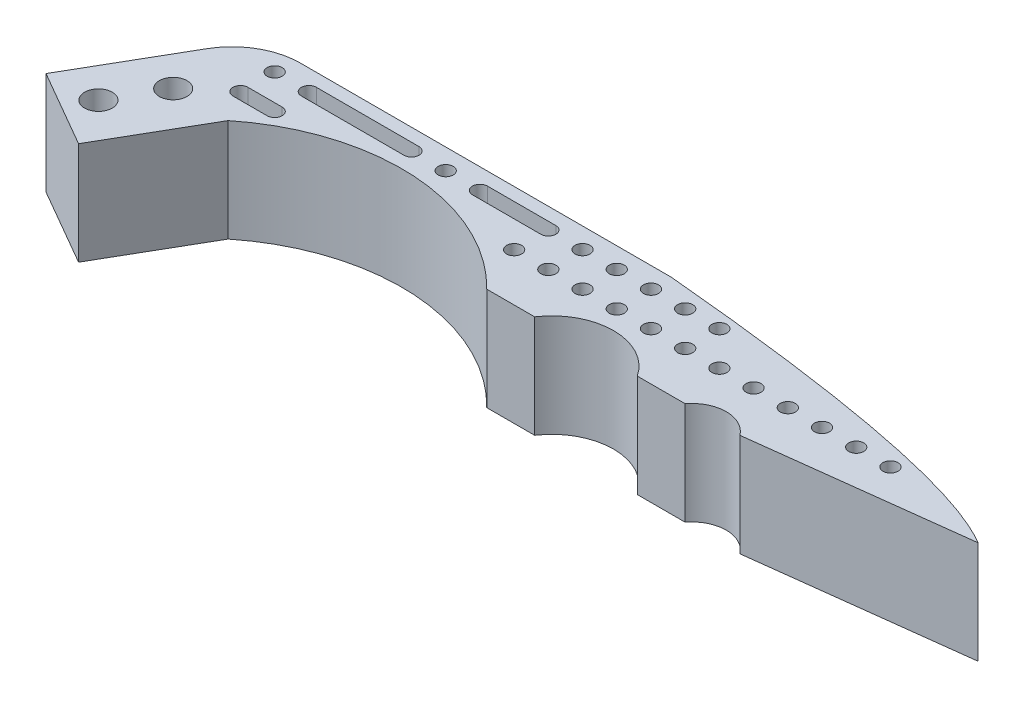
SolidWorks part; units mm, degrees
ref_plane "前视基准面" through (0, 0, 0) normal (0, 0, 1) x (1, 0, 0)
ref_plane "上视基准面" through (0, 0, 0) normal (0, 1, 0) x (1, 0, 0)
ref_plane "右视基准面" through (0, 0, 0) normal (1, 0, 0) x (0, 0, -1)
other "Configuration Table"
sketch "草图1" plane through (0, 0, 0) normal (0, 1, 0) x (1, 0, 0)
  line L0 (0, 0) -> (60, 0)
  line L1 (60, 0) -> (120, 0) construction
  line L2 (120, 0) -> (120, -15) construction
  line L3 (60, 0) -> (115, -5) construction
  line L4 (115, -5) -> (120, -15) construction
  line L5 (120, -15) -> (85, -15)
  line L6 (85, -15) -> (77, -15) construction
  line L7 (77, -15) -> (70, -15)
  line L8 (70, -15) -> (55, -15)
  line L9 (55, -15) -> (48, -15)
  line L10 (0, 0) -> (0, -24.7218) construction
  line L11 (0, 0) -> (-11.5, -19.9186)
  line L16 (-11.5, -19.9186) -> (-0.2417, -26.4186)
  line L17 (-0.2417, -26.4186) -> (7.7583, -12.5622)
  arc A0 (55, -15) -> (70, -15) centre (62.5, -19.9749) cw
  arc A1 (77, -15) -> (85, -15) centre (81, -18) cw
  arc A2 (7.7583, -12.5622) -> (48, -15) centre (26.5356, -35.959) cw
  spline S0 degree 2 poles (60, 0) (115, -5) (120, -15) knots 0 0 0 1 1 1
  point P3 (81, -15)
  dimension "D9" = 15
  dimension "D12" = 7
  dimension "D13" = 13
  dimension "D11" = 23
  dimension "D10" = 30
  dimension "D14" = 16
  dimension "D1" = 60
  dimension "D2" = 60
  dimension "D3" = 5
  dimension "D4" = 5
  dimension "D5" = 15
  dimension "D6" = 35
  dimension "D7" = 8
  dimension "D8" = 7
extrude "凸台-拉伸1" add sketch "草图1" along normal blind 15
sketch "草图2" plane through (0, 15, 0) normal (0, 1, 0) x (1, 0, 0)
  line L1 (120, -15) -> (85, -15) construction
  line L15 (0, 0) -> (60, 0) construction
  line L18 (0, 0) -> (-11.5, -19.9186) construction
  line L26 (-11.5, -19.9186) -> (-0.2417, -26.4186) construction
  line L27 (-4.3038, -19.4545) -> (-0.3038, -12.5263) construction
  line L30 (10, -4.1) -> (25, -4.1)
  line L31 (25, -1.9) -> (10, -1.9)
  line L32 (35, -1.9) -> (45, -1.9)
  line L33 (35, -4.1) -> (45, -4.1)
  line L34 (5, -6.9) -> (10, -6.9)
  line L35 (5, -9.1) -> (10, -9.1)
  circle A0 centre (5, -3) radius 1.1
  arc A1 (10, -1.9) -> (10, -4.1) centre (10, -3) ccw
  arc A4 (25, -4.1) -> (25, -1.9) centre (25, -3) ccw
  circle A5 centre (30, -3) radius 1.1
  arc A6 (35, -1.9) -> (35, -4.1) centre (35, -3) ccw
  arc A8 (45, -4.1) -> (45, -1.9) centre (45, -3) ccw construction
  circle A10 centre (55, -3) radius 1.1
  circle A11 centre (60, -3) radius 1.1
  arc A12 (5, -6.9) -> (5, -9.1) centre (5, -8) ccw
  arc A13 (10, -9.1) -> (10, -6.9) centre (10, -8) ccw
  circle A14 centre (45, -8) radius 1.1
  circle A15 centre (50, -8) radius 1.1
  circle A16 centre (55, -8) radius 1.1
  circle A17 centre (60, -8) radius 1.1
  circle A18 centre (65, -3) radius 1.1
  circle A19 centre (65, -8) radius 1.1
  circle A20 centre (70, -8) radius 1.1
  circle A21 centre (75, -8) radius 1.1
  circle A26 centre (70, -3) radius 1.1
  circle A28 centre (-4.3038, -19.4545) radius 2.02
  arc A31 (15, -4.1) -> (15, -1.9) centre (15, -3) ccw [skipped]
  arc A32 (20, -4.1) -> (20, -1.9) centre (20, -3) ccw [skipped]
  circle A33 centre (50, -3) radius 1.1
  arc A34 (45, -4.1) -> (45, -1.9) centre (45, -3) ccw
  arc A35 (40, -1.9) -> (40, -4.1) centre (40, -3) ccw construction
  arc A36 (50, -4.1) -> (50, -1.9) centre (50, -3) ccw [skipped]
  circle A37 centre (-0.3038, -12.5263) radius 2.02
  circle A38 centre (80, -8) radius 1.1
  circle A39 centre (85, -8) radius 1.1
  circle A40 centre (90, -8) radius 1.1
  circle A41 centre (95, -8) radius 1.1
  circle A42 centre (100, -8) radius 1.1
  point P8 (-5.8708, -23.1686)
  point P52 (-4.3038, -19.4545)
  dimension "D3" = 2
  dimension "D16" = 8
  dimension "D18" = 5
  dimension "D4" = 6
  dimension "D9" = 6
  dimension "D10" = 4
  dimension "D11" = 2
  dimension "D14" = 5
  dimension "D15" = 3
  dimension "D2" = 12
  dimension "D12" = 2
  dimension "D13" = 3
extrude "切除-拉伸1" cut sketch "草图2" against normal up to surface (15 mm away) up to face at (43.7716, 0, 11.6006)
sketch "草图4" plane through (0, 15, 0) normal (0, 1, 0) x (1, 0, 0)
  line L0 (85, -15) -> (115.9913, -11.1948)
  line L1 (120, -15) -> (85, -15) construction
  line L2 (85, -15) -> (120, -15)
  line L3 (120, -15) -> (120, -11.1948)
  line L4 (120, -11.1948) -> (115.9913, -11.1948)
  parabola Q0 (60, 0) -> (120, -15) focus (118.3168, -16.8317) apex (120.4784, -16.6155) construction
  dimension "D1" = 7
extrude "切除-拉伸2" cut sketch "草图4" against normal up to next
fillet "圆角1" radius 10 1 edges at (0, 7.5, 0)
